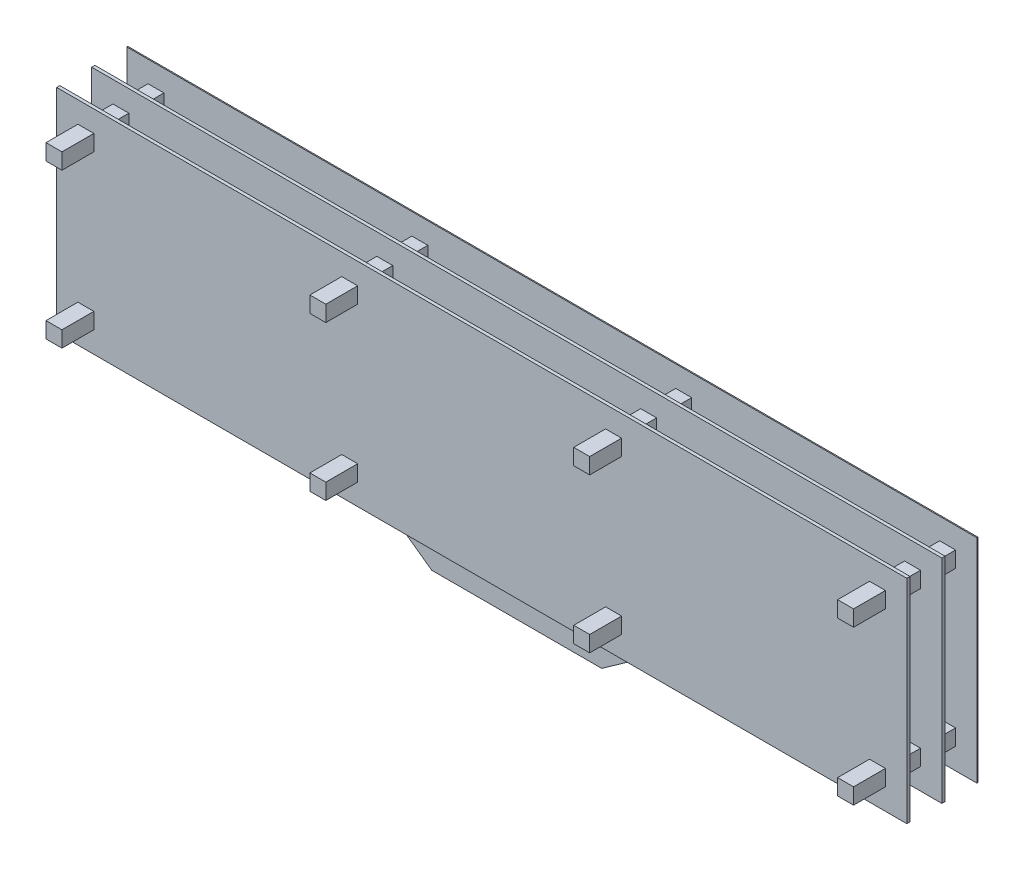
SolidWorks part; units mm, degrees
ref_plane "Front Plane" through (0, 0, 0) normal (0, 0, 1) x (1, 0, 0)
ref_plane "Top Plane" through (0, 0, 0) normal (0, 1, 0) x (1, 0, 0)
ref_plane "Right Plane" through (0, 0, 0) normal (1, 0, 0) x (0, 0, -1)
sketch "Sketch1" plane through (0, 0, 0) normal (0, 0, 1) x (1, 0, 0)
  line L1 (-40, -10) -> (40, -10)
  line L2 (-40, -10) -> (-40, 10)
  line L3 (-40, 10) -> (40, 10)
  line L4 (40, -10) -> (40, 10)
  line L5 (0, 10) -> (0, -10) construction
  line L6 (-40, 0) -> (40, 0) construction
  point P0 (0, 0)
  dimension "D1" = 80
  dimension "D2" = 20
extrude "Boss-Extrude1" add sketch "Sketch1" along normal blind 0.1
sketch "Sketch3" plane through (0, 0, 0.1) normal (0, 0, 1) x (1, 0, 0)
  line L0 (40, 10) -> (-40, 10) construction
  line L1 (-38, 6.5) -> (-36.5, 6.5)
  line L2 (-38, 6.5) -> (-38, 8)
  line L3 (-38, 8) -> (-36.5, 8)
  line L4 (-36.5, 6.5) -> (-36.5, 8)
  line L5 (-37.25, 8) -> (-37.25, 6.5) construction
  line L6 (-38, 7.25) -> (-36.5, 7.25) construction
  line L11 (-13.17, 6.5) -> (-13.17, 8)
  line L12 (-13.17, 6.5) -> (-11.67, 6.5)
  line L17 (-11.67, 6.5) -> (-11.67, 8)
  line L18 (-13.17, 8) -> (-11.67, 8)
  line L23 (11.66, 6.5) -> (11.66, 8)
  line L24 (11.66, 6.5) -> (13.16, 6.5)
  line L29 (13.16, 6.5) -> (13.16, 8)
  line L30 (11.66, 8) -> (13.16, 8)
  line L35 (36.49, 6.5) -> (36.49, 8)
  line L36 (36.49, 6.5) -> (37.99, 6.5)
  line L41 (37.99, 6.5) -> (37.99, 8)
  line L42 (36.49, 8) -> (37.99, 8)
  line L47 (-13.17, -8) -> (-13.17, -6.5)
  line L48 (-13.17, -8) -> (-11.67, -8)
  line L49 (-40, 10) -> (-40, -10) construction
  line L50 (-11.67, -8) -> (-11.67, -6.5)
  line L51 (-13.17, -6.5) -> (-11.67, -6.5)
  line L52 (11.66, -8) -> (11.66, -6.5)
  line L53 (11.66, -8) -> (13.16, -8)
  line L54 (13.16, -8) -> (13.16, -6.5)
  line L55 (11.66, -6.5) -> (13.16, -6.5)
  line L56 (36.49, -8) -> (36.49, -6.5)
  line L57 (36.49, -8) -> (37.99, -8)
  line L58 (37.99, -8) -> (37.99, -6.5)
  line L59 (36.49, -6.5) -> (37.99, -6.5)
  line L60 (-38, -8) -> (-38, -6.5)
  line L61 (-38, -8) -> (-36.5, -8)
  line L62 (-36.5, -8) -> (-36.5, -6.5)
  line L63 (-38, -6.5) -> (-36.5, -6.5)
  line L64 (-38, 6.5) -> (-13.17, 6.5) construction
  line L65 (-40, -10) -> (40, -10) construction
  point P0 (-37.25, 7.25)
  dimension "D1" = 1.5
  dimension "D2" = 1.5
  dimension "D3" = 2
  dimension "D4" = 2
  dimension "D7" = 24.83
  dimension "D8" = 2
  dimension "D9" = 2
  dimension "D5" = 4
  dimension "D6" = 2
extrude "Boss-Extrude2" add sketch "Sketch3" along normal blind 3
sketch "Sketch4" plane through (0, 0, 3.1) normal (0, 0, 1) x (1, 0, 0)
  line L0 (40, -10) -> (40, 10) construction
  line L1 (-40, 10) -> (40, 10)
  line L2 (-40, 10) -> (-40, -10)
  line L4 (40, 10) -> (40, -10)
  line L5 (-40, -10) -> (40, -10) construction
  line L6 (-40, -10) -> (-15, -10)
  line L7 (-15, -10) -> (-8, -15)
  line L8 (-8, -15) -> (8, -15)
  line L9 (8, -15) -> (15, -10)
  line L10 (15, -10) -> (40, -10)
  point P9 (0, -15)
  dimension "D1" = 25
  dimension "D2" = 25
  dimension "D3" = 16
  dimension "D4" = 5
extrude "Boss-Extrude3" add sketch "Sketch4" along normal blind 0.3
pattern_linear "LPattern1" count 2 spacing 3.3 along (0, 0, 1) of "Boss-Extrude2"
sketch "Sketch6" plane through (0, 0, 6.4) normal (0, 0, 1) x (1, 0, 0)
  line L1 (-40, 10) -> (40, 10)
  line L2 (-40, 10) -> (-40, -10)
  line L3 (-40, -10) -> (40, -10)
  line L4 (40, 10) -> (40, -10)
extrude "Boss-Extrude4" add sketch "Sketch6" along normal blind 0.3
pattern_linear "LPattern3" count 2 spacing 3.3 along (0, 0, 1) of "LPattern1"
scale "Scale1" scale about origin uniform scaling yes scale factor 1000
equation "\"D2@Sketch4\"=\"D1@Sketch4\""
